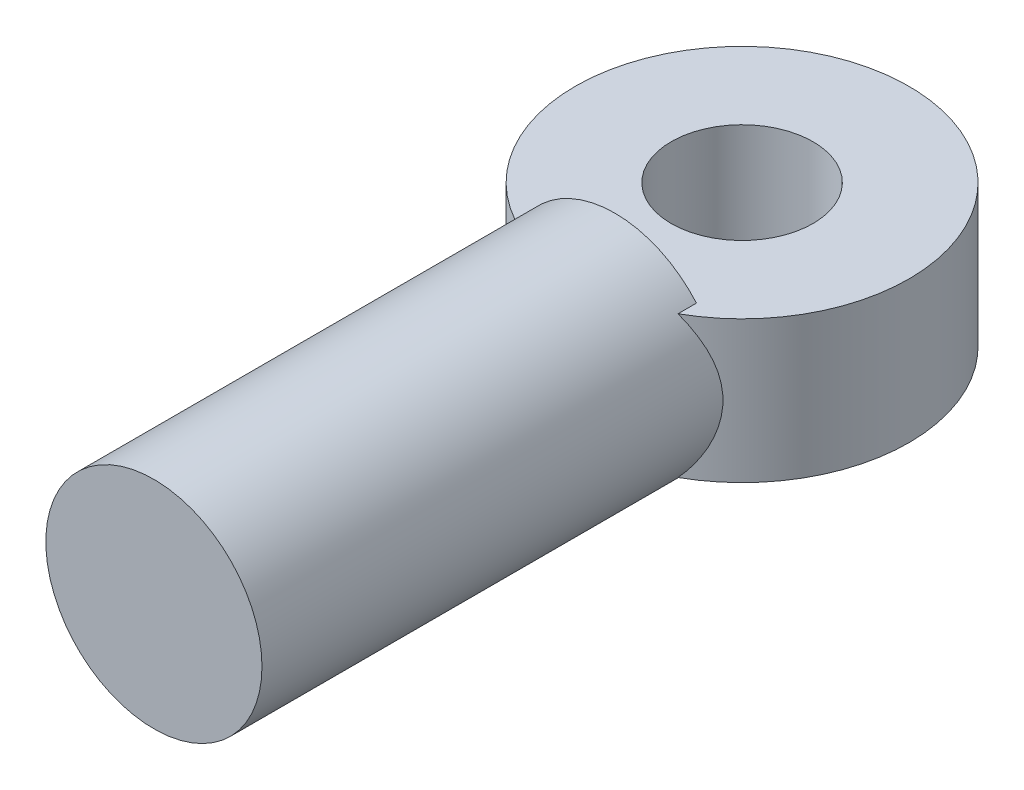
SolidWorks part; units mm, degrees
ref_plane "Front Plane" through (0, 0, 0) normal (0, 0, 1) x (1, 0, 0)
ref_plane "Top Plane" through (0, 0, 0) normal (0, 1, 0) x (1, 0, 0)
ref_plane "Right Plane" through (0, 0, 0) normal (1, 0, 0) x (0, 0, -1)
sketch "Sketch1" plane through (0, 0, 0) normal (0, 0, 1) x (1, 0, 0)
  circle A0 centre (0, 0) radius 30.475
  dimension "D1" = 60.95
extrude "Boss-Extrude1" add sketch "Sketch1" along normal blind 130
sketch "Sketch2" plane through (0, 0, 0) normal (0, 1, 0) x (1, 0, 0)
  line L0 (0, 0) -> (0, 71.7161) construction
  circle A0 centre (0, 35.8581) radius 47.0587
extrude "Boss-Extrude2" add sketch "Sketch2" along normal mid plane 40
sketch "Sketch8" plane through (0, 20, 0) normal (0, 1, 0) x (1, 0, 0)
  circle A0 centre (0, 35.8581) radius 20
  dimension "D1" = 40
sketch "Sketch10" plane through (0, 20, 0) normal (0, 1, 0) x (1, 0, 0)
extrude "Cut-Extrude1" cut sketch "Sketch8" against normal blind 40 contours A0
